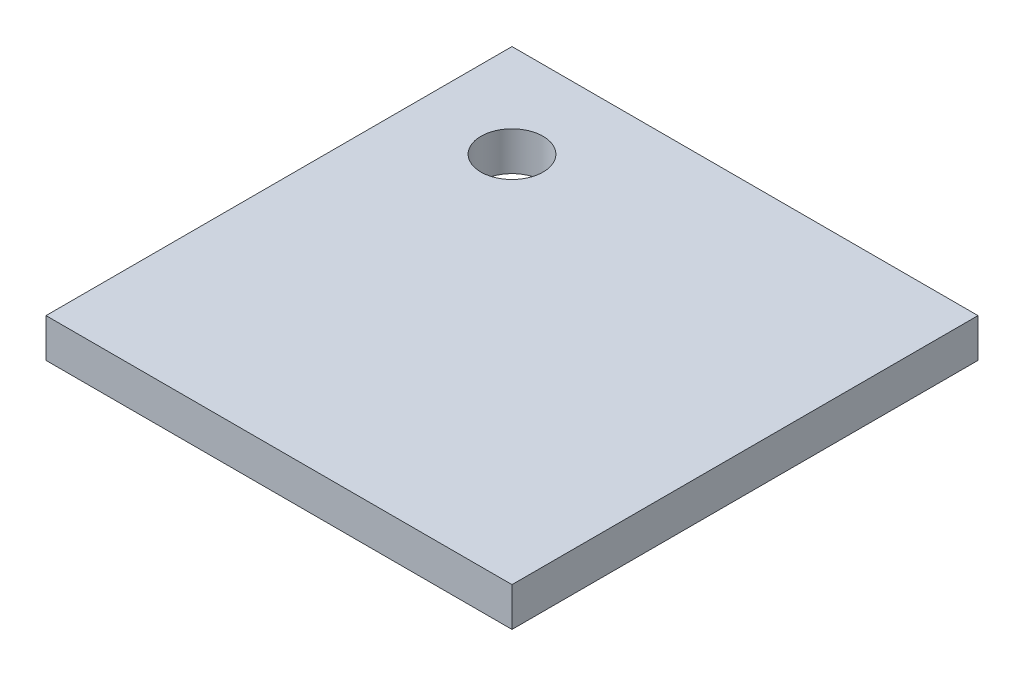
SolidWorks part; units mm, degrees
ref_plane "前视基准面" through (0, 0, 0) normal (0, 0, 1) x (1, 0, 0)
ref_plane "上视基准面" through (0, 0, 0) normal (0, 1, 0) x (1, 0, 0)
ref_plane "右视基准面" through (0, 0, 0) normal (1, 0, 0) x (0, 0, -1)
sketch "草图1" plane through (0, 0, 0) normal (0, 1, 0) x (1, 0, 0)
  line L1 (0, 0) -> (60, 0)
  line L2 (0, 0) -> (0, -60)
  line L3 (0, -60) -> (60, -60)
  line L4 (60, 0) -> (60, -60)
  circle A0 centre (12, -12) radius 4
  dimension "D1" = 8
  dimension "D2" = 12
  dimension "D3" = 12
  dimension "D4" = 60
  dimension "D5" = 60
extrude "凸台-拉伸1" add sketch "草图1" along normal blind 5
